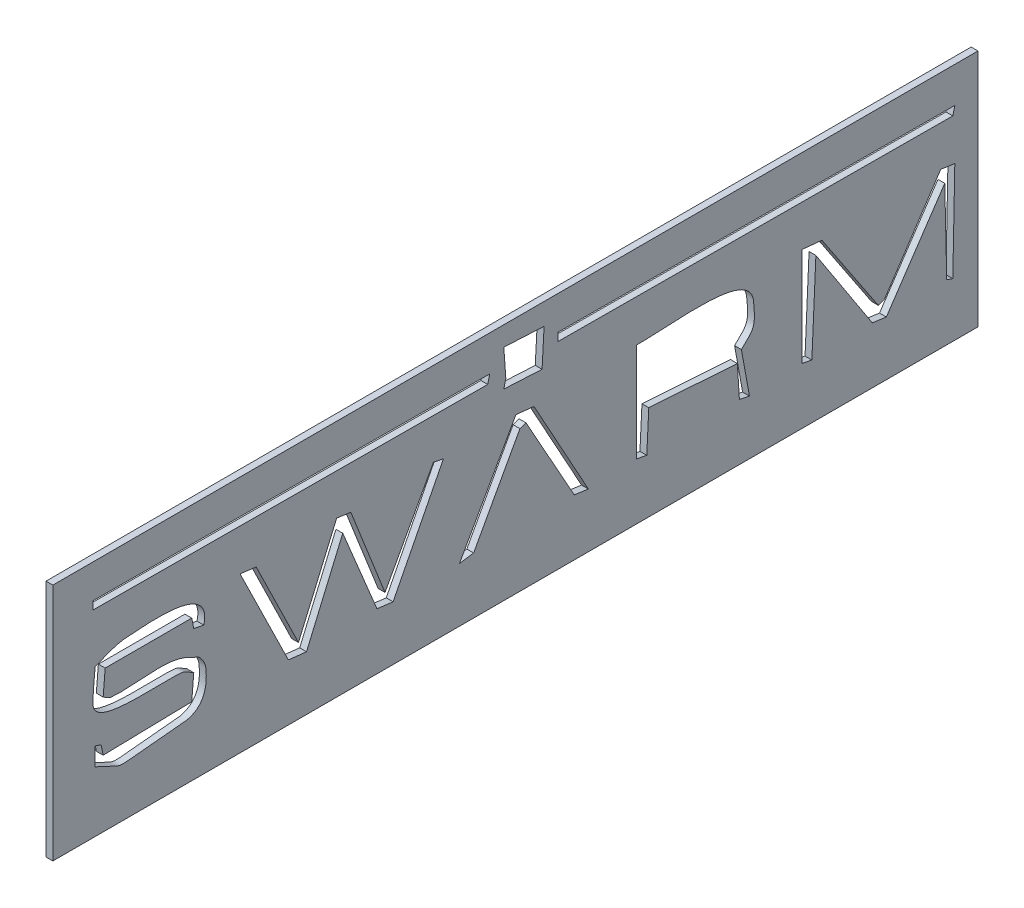
SolidWorks part; units mm, degrees
ref_plane "Front Plane" through (0, 0, 0) normal (0, 0, 1) x (1, 0, 0)
ref_plane "Top Plane" through (0, 0, 0) normal (0, 1, 0) x (1, 0, 0)
ref_plane "Right Plane" through (0, 0, 0) normal (1, 0, 0) x (0, 0, -1)
sketch "Sketch1" plane through (0, 0, 0) normal (1, 0, 0) x (0, 0, -1)
  line L0 (77.8972, 63.0517) -> (389.4859, 63.0517) construction
  line L1 (127.6641, -67.7691) -> (439.2528, -67.7691) construction
  line L2 (77.8972, 63.0517) -> (389.4859, 63.0517) construction
  line L3 (209.6118, 101.9986) -> (228.3272, 101.0628)
  line L4 (228.3272, 101.0628) -> (227.3914, 84.219)
  line L5 (227.3914, 84.219) -> (209.6118, 85.1548)
  line L6 (209.6118, 85.1548) -> (210.5476, 88.8979)
  line L7 (210.5476, 88.8979) -> (209.6118, 101.9986)
  line L8 (18.7153, 95.4482) -> (203.0614, 94.5125)
  line L9 (203.0614, 94.5125) -> (202.1257, 90.7694)
  line L10 (202.1257, 90.7694) -> (18.7153, 91.7052)
  line L11 (18.7153, 91.7052) -> (18.7153, 95.4482)
  line L12 (234.8775, 95.4482) -> (419.2236, 94.5125)
  line L13 (419.2236, 94.5125) -> (418.2879, 90.7694)
  line L14 (418.2879, 90.7694) -> (234.8775, 91.7052)
  line L15 (234.8775, 91.7052) -> (234.8775, 95.4482)
  line L16 (70.1825, 59.8891) -> (65.5037, 60.8249)
  line L17 (65.5037, 60.8249) -> (64.5679, 65.5037)
  line L18 (64.5679, 65.5037) -> (24.3299, 65.5037)
  line L19 (24.3299, 65.5037) -> (23.3942, 54.2745)
  line L20 (19.6511, 28.073) -> (19.6511, 36.4949)
  line L21 (19.6511, 36.4949) -> (22.4584, 35.5591)
  line L22 (22.4584, 35.5591) -> (23.3942, 30.8803)
  line L23 (23.3942, 30.8803) -> (64.5679, 31.8161)
  line L24 (64.5679, 31.8161) -> (65.5037, 43.0453)
  line L25 (87.0263, 72.0541) -> (94.5125, 71.1183)
  line L26 (94.5125, 71.1183) -> (114.1636, 30.8803)
  line L27 (114.1636, 30.8803) -> (131.9431, 72.0541)
  line L28 (131.9431, 72.0541) -> (138.4935, 71.1183)
  line L29 (138.4935, 71.1183) -> (154.4016, 30.8803)
  line L30 (154.4016, 30.8803) -> (176.86, 72.0541)
  line L31 (176.86, 72.0541) -> (181.5388, 71.1183)
  line L32 (181.5388, 71.1183) -> (158.1446, 25.2657)
  line L33 (158.1446, 25.2657) -> (150.6585, 26.2015)
  line L34 (150.6585, 26.2015) -> (134.7505, 64.5679)
  line L35 (134.7505, 64.5679) -> (117.9066, 25.2657)
  line L36 (117.9066, 25.2657) -> (109.4847, 26.2015)
  line L37 (109.4847, 26.2015) -> (87.0263, 72.0541)
  line L38 (215.2264, 72.0541) -> (223.6483, 71.1183)
  line L39 (223.6483, 71.1183) -> (248.914, 25.2657)
  line L40 (248.914, 25.2657) -> (242.3637, 26.2015)
  line L41 (242.3637, 26.2015) -> (219.9052, 66.4395)
  line L42 (219.9052, 66.4395) -> (217.0979, 65.5037)
  line L43 (217.0979, 65.5037) -> (195.5753, 26.2015)
  line L44 (195.5753, 26.2015) -> (189.0249, 25.2657)
  line L45 (189.0249, 25.2657) -> (215.2264, 72.0541)
  line L46 (320.0323, 45.8526) -> (323.7754, 25.2657)
  line L47 (323.7754, 25.2657) -> (319.0966, 26.2015)
  line L48 (319.0966, 26.2015) -> (318.1608, 41.1737)
  line L49 (318.1608, 41.1737) -> (276.987, 43.981)
  line L50 (276.987, 43.981) -> (276.0513, 25.2657)
  line L51 (276.0513, 25.2657) -> (271.3724, 26.2015)
  line L52 (271.3724, 26.2015) -> (271.3724, 72.0541)
  line L53 (348.1053, 72.0541) -> (357.463, 71.1183)
  line L54 (357.463, 71.1183) -> (383.6645, 31.8161)
  line L55 (383.6645, 31.8161) -> (386.4718, 32.7518)
  line L56 (386.4718, 32.7518) -> (412.6733, 72.0541)
  line L57 (412.6733, 72.0541) -> (419.2236, 71.1183)
  line L58 (419.2236, 71.1183) -> (418.2879, 25.2657)
  line L59 (418.2879, 25.2657) -> (415.4806, 26.2015)
  line L60 (415.4806, 26.2015) -> (414.5448, 65.5037)
  line L61 (414.5448, 65.5037) -> (387.4075, 25.2657)
  line L62 (387.4075, 25.2657) -> (380.8572, 26.2015)
  line L63 (380.8572, 26.2015) -> (354.6557, 66.4395)
  line L64 (354.6557, 66.4395) -> (352.7842, 25.2657)
  line L65 (352.7842, 25.2657) -> (348.1053, 26.2015)
  line L66 (348.1053, 26.2015) -> (348.1053, 72.0541)
  line L68 (0, 111.0621) -> (430, 111.0621)
  line L69 (0, 111.0621) -> (0, 0)
  line L70 (0, 0) -> (430, 0)
  line L71 (430, 111.0621) -> (430, 0)
  spline S0 degree 3 poles (19.6511, 68.311) (24.7315, 70.4883) (30.0337, 72.8481) (35.5591, 72.9898) (41.5745, 73.1441) (74.6016, 77.5655) (70.1825, 59.8891) knots 0 0 0 0 1 1 1 2 2 2 2
  spline S1 degree 3 poles (23.3942, 54.2745) (24.6419, 53.6506) (25.7483, 52.5322) (27.1372, 52.403) (39.5954, 51.2441) (53.839, 56.033) (64.5679, 49.5957) (65.7641, 48.878) (67.3924, 48.7739) (68.311, 47.7241) (69.6889, 46.1494) (70.8872, 44.1892) (71.1183, 42.1095) (72.1016, 33.26) (69.5815, 25.9749) (59.8891, 25.2657) (22.7294, 22.5467) (37.0783, 20.6042) (19.6511, 28.073) knots 0 0 0 0 1 1 1 2 2 2 3 3 3 4 4 4 5 5 5 6 6 6 6
  spline S2 degree 3 poles (65.5037, 43.0453) (63.6322, 43.981) (61.9681, 45.6163) (59.8891, 45.8526) (49.3778, 47.047) (19.2363, 42.9194) (18.7153, 53.3387) (18.4656, 58.333) (19.3392, 63.3202) (19.6511, 68.311) knots 0 0 0 0 1 1 1 2 2 2 3 3 3 3
  spline S3 degree 3 poles (271.3724, 72.0541) (287.5062, 71.7248) (324.0568, 77.803) (325.6469, 62.6964) (326.8518, 51.25) (325.8187, 51.639) (320.0323, 45.8526) knots 0 0 0 0 1 1 1 2 2 2 2
  dimension "D1" = 430
extrude "Boss-Extrude1" add sketch "Sketch1" along normal blind 3.175
